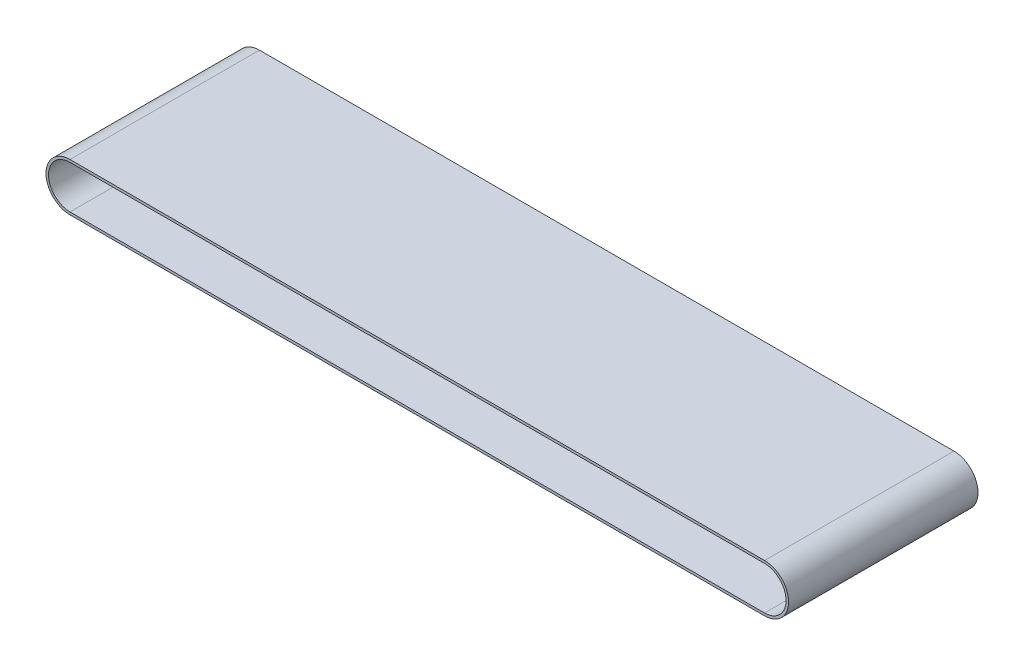
SolidWorks part; units mm, degrees
ref_plane "Front Plane" through (0, 0, 0) normal (0, 0, 1) x (1, 0, 0)
ref_plane "Top Plane" through (0, 0, 0) normal (0, 1, 0) x (1, 0, 0)
ref_plane "Right Plane" through (0, 0, 0) normal (1, 0, 0) x (0, 0, -1)
sketch "Sketch1" plane through (0, 0, 0) normal (0, 0, 1) x (1, 0, 0)
  line L0 (0, 18) -> (550, 18)
  line L1 (0, -18) -> (550, -18)
  arc A0 (0, 18) -> (0, -18) centre (0, 0) ccw
  arc A1 (550, -18) -> (550, 18) centre (550, 0) ccw
  dimension "D1" = 36
  dimension "D2" = 550
extrude "Boss-Extrude1" add sketch "Sketch1" along normal blind 150
sketch "Sketch2" plane through (0, 0, 150) normal (0, 0, 1) x (1, 0, 0)
  line L6 (0, -16) -> (550, -16)
  line L7 (550, 16) -> (0, 16)
  line L8 (0, -16) -> (550, -16)
  line L9 (550, 16) -> (0, 16)
  arc A6 (0, 16) -> (0, -16) centre (0, 0) ccw
  arc A7 (550, -16) -> (550, 16) centre (550, 0) ccw
  arc A8 (0, 16) -> (0, -16) centre (0, 0) ccw
  arc A9 (550, -16) -> (550, 16) centre (550, 0) ccw
  dimension "D1" = 2
extrude "Cut-Extrude1" cut sketch "Sketch2" against normal blind 150 contours L9 A8 L8 A9
sketch "Sketch3" plane through (0, 0, 150) normal (0, 0, 1) x (1, 0, 0)
  line L4 (0, -20) -> (550, -20)
  line L5 (550, 20) -> (0, 20)
  line L6 (0, -20) -> (550, -20)
  line L7 (550, 20) -> (0, 20)
  arc A4 (0, 20) -> (0, -20) centre (0, 0) ccw
  arc A5 (550, -20) -> (550, 20) centre (550, 0) ccw
  arc A6 (0, 20) -> (0, -20) centre (0, 0) ccw
  arc A7 (550, -20) -> (550, 20) centre (550, 0) ccw
  dimension "D1" = 2
extrude "Boss-Extrude2" add sketch "Sketch3" against normal up to surface (150 mm away) up to face at (275, 0, 0)
sketch "Sketch4" plane through (0, 0, 150) normal (0, 0, 1) x (1, 0, 0)
  line L4 (0, -18) -> (550, -18)
  line L5 (550, 18) -> (0, 18)
  line L6 (0, -18) -> (550, -18)
  line L7 (550, 18) -> (0, 18)
  arc A4 (0, 18) -> (0, -18) centre (0, 0) ccw
  arc A5 (550, -18) -> (550, 18) centre (550, 0) ccw
  arc A6 (0, 18) -> (0, -18) centre (0, 0) ccw
  arc A7 (550, -18) -> (550, 18) centre (550, 0) ccw
  dimension "D1" = 2
extrude "Cut-Extrude2" cut sketch "Sketch4" against normal blind 168
sketch "Sketch5" plane through (0, 0, 150) normal (0, 0, 1) x (1, 0, 0)
  line L4 (0, -18) -> (550, -18)
  line L5 (550, 18) -> (0, 18)
  line L6 (0, -18) -> (550, -18)
  line L7 (550, 18) -> (0, 18)
  arc A4 (0, 18) -> (0, -18) centre (0, 0) ccw
  arc A5 (550, -18) -> (550, 18) centre (550, 0) ccw
  arc A6 (0, 18) -> (0, -18) centre (0, 0) ccw
  arc A7 (550, -18) -> (550, 18) centre (550, 0) ccw
  dimension "D1" = 2
extrude "Boss-Extrude4" add sketch "Sketch5" against normal up to surface (150 mm away) contours A6 L6 A7 L7 up to face at (275, 0, 0)
sketch "Sketch7" plane through (0, 0, 150) normal (0, 0, 1) x (1, 0, 0)
  line L4 (0, -17) -> (550, -17)
  line L5 (550, 17) -> (0, 17)
  line L6 (0, -17) -> (550, -17)
  line L7 (550, 17) -> (0, 17)
  arc A4 (0, 17) -> (0, -17) centre (0, 0) ccw
  arc A5 (550, -17) -> (550, 17) centre (550, 0) ccw
  arc A6 (0, 17) -> (0, -17) centre (0, 0) ccw
  arc A7 (550, -17) -> (550, 17) centre (550, 0) ccw
  dimension "D1" = 3
extrude "Cut-Extrude3" cut sketch "Sketch7" against normal blind 225
sketch "Sketch8" plane through (0, 0, 150) normal (0, 0, 1) x (1, 0, 0)
  line L0 (0, 0) -> (550, 0) construction
  line L1 (0, 20) -> (550, 20)
  line L2 (0, -20) -> (550, -20)
  line L3 (0, 0) -> (550, 0) construction
  line L4 (0, 19) -> (550, 19)
  line L5 (0, -19) -> (550, -19)
  arc A0 (0, 20) -> (0, -20) centre (0, 0) ccw
  arc A1 (550, -20) -> (550, 20) centre (550, 0) ccw
  arc A2 (550, -20) -> (550, 20) centre (550, 0) ccw construction
  arc A3 (0, 19) -> (0, -19) centre (0, 0) ccw
  arc A4 (550, -19) -> (550, 19) centre (550, 0) ccw
  point P4 (275, 0)
  point P14 (275, 0)
  dimension "D1" = 19
extrude "Cut-Extrude4" cut sketch "Sketch8" against normal blind 225
